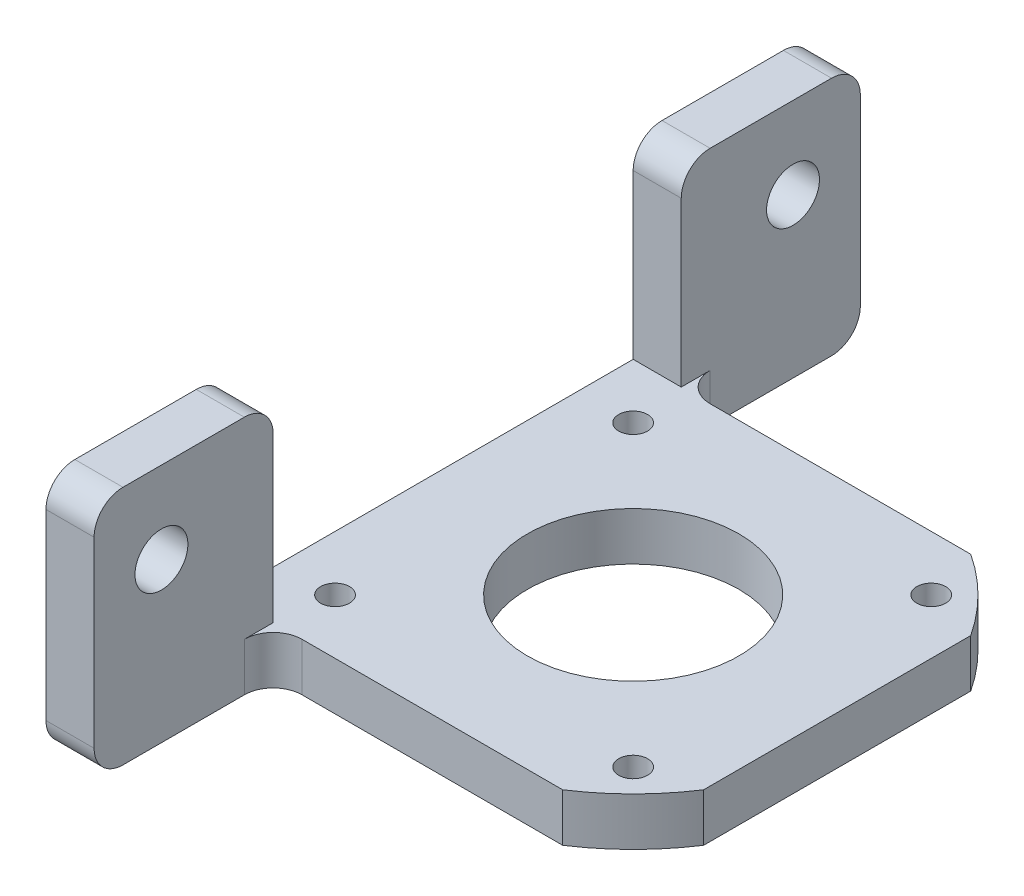
SolidWorks part; units mm, degrees
ref_plane "Front Plane" through (0, 0, 0) normal (0, 0, 1) x (1, 0, 0)
ref_plane "Top Plane" through (0, 0, 0) normal (0, 1, 0) x (1, 0, 0)
ref_plane "Right Plane" through (0, 0, 0) normal (1, 0, 0) x (0, 0, -1)
sketch "Sketch1" plane through (0, 0, 0) normal (0, 1, 0) x (1, 0, 0)
  line L0 (-13.8838, -21.209) -> (-21.209, -21.209)
  line L1 (-21.209, -21.209) -> (-21.209, -13.8838)
  line L2 (-21.209, 13.8838) -> (-21.209, 21.209)
  line L3 (-21.209, 21.209) -> (-13.8838, 21.209)
  line L5 (-21.209, -13.8838) -> (-21.209, 13.8838)
  line L6 (13.8838, 21.209) -> (-13.8838, 21.209)
  line L7 (21.209, -13.8838) -> (21.209, 13.8838)
  line L8 (13.8838, -21.209) -> (-13.8838, -21.209)
  arc A2 (21.209, 13.8838) -> (13.8838, 21.209) centre (0, 0) ccw
  arc A3 (13.8838, -21.209) -> (21.209, -13.8838) centre (0, 0) ccw
  dimension "D1" = 25.3492
  dimension "D2" = 21.209
sketch "Sketch3" plane through (0, 0, 0) normal (0, 1, 0) x (1, 0, 0)
  line L1 (21.209, -21.209) -> (-21.209, -21.209) construction
  line L2 (21.209, -21.209) -> (21.209, 21.209) construction
  line L3 (21.209, 21.209) -> (-21.209, 21.209) construction
  line L4 (-21.209, -21.209) -> (-21.209, 21.209) construction
  line L5 (21.209, -21.209) -> (-21.209, 21.209) construction
  line L6 (21.209, 21.209) -> (-21.209, -21.209) construction
  line L7 (15.494, -15.494) -> (-15.494, -15.494) construction
  line L8 (15.494, -15.494) -> (15.494, 15.494) construction
  line L9 (15.494, 15.494) -> (-15.494, 15.494) construction
  line L10 (-15.494, -15.494) -> (-15.494, 15.494) construction
  line L11 (15.494, -15.494) -> (-15.494, 15.494) construction
  line L12 (15.494, 15.494) -> (-15.494, -15.494) construction
  circle A0 centre (-15.494, 15.494) radius 1.5 construction
  circle A1 centre (15.494, 15.494) radius 1.5 construction
  circle A2 centre (-15.494, -15.494) radius 1.5 construction
  circle A3 centre (15.494, -15.494) radius 1.5 construction
  circle A4 centre (0, 0) radius 2.5 construction
  circle A5 centre (0, 0) radius 10.9982 construction
  circle A6 centre (15.494, -15.494) radius 1.5
  circle A7 centre (15.494, 15.494) radius 1.5
  circle A8 centre (-15.494, -15.494) radius 1.5
  circle A9 centre (-15.494, 15.494) radius 1.5
  circle A10 centre (0, 0) radius 10.9982
  point P0 (0, 0)
  point P6 (0, 0)
  point P18 (0, 2.5)
  point P19 (0, 21.209)
  point P20 (0, 10.9982)
  point P21 (-15.494, -16.994)
  dimension "D3" = 3
  dimension "ShaftDia" = 5
  dimension "LargeDia" = 21.9964
  dimension "Width" = 42.418
  dimension "CentertoCenter" = 30.988
extrude "Boss-Extrude1" add sketch "Sketch1" along normal blind 5 contours L6 L3 L2 L5 L1 L0 L8 A3 L7 A2
extrude "Cut-Extrude1" cut sketch "Sketch3" along normal blind 5
sketch "Sketch5" plane through (0, 0, 21.209) normal (0, 0, 1) x (1, 0, 0)
  line L0 (-21.209, 5) -> (-21.209, 0)
  line L1 (-21.209, 0) -> (-16.209, 0)
  line L2 (-16.209, 0) -> (-16.209, 5)
  line L3 (13.8838, 5) -> (-21.209, 5) construction
  line L4 (-16.209, 5) -> (-21.209, 5)
  dimension "D1" = 5
extrude "Boss-Extrude2" add sketch "Sketch5" along normal blind 18.62
ref_plane "Plane1" through (0, 0, 0) normal (0, 0, -1) x (-1, 0, 0)
sketch "Sketch6" plane through (0, 5, 0) normal (0, 1, 0) x (1, 0, 0)
  line L0 (-16.209, -21.209) -> (-21.209, -21.209)
  line L1 (-21.209, -39.829) -> (-21.209, 21.209) construction
  line L2 (-21.209, -21.209) -> (-21.209, -39.829)
  line L3 (-21.209, -39.829) -> (-16.209, -39.829)
  line L4 (-16.209, -39.829) -> (-16.209, -21.209)
extrude "Boss-Extrude3" add sketch "Sketch6" along normal blind 20
sketch "Sketch7" plane through (-16.209, 0, 0) normal (1, 0, 0) x (0, 0, -1)
  line L0 (-39.829, 0) -> (-21.209, 0) construction
  line L1 (-39.829, 0) -> (-39.829, 25) construction
  circle A0 centre (-32.829, 16.5) radius 2.75
  dimension "D3" = 5.5
  dimension "D1" = 16.5
  dimension "D2" = 7
extrude "Cut-Extrude2" cut sketch "Sketch7" against normal up to next
mirror "Mirror3" about plane through (0, 0, 0) normal (0, 0, -1) of "Boss-Extrude2", "Boss-Extrude3", "Cut-Extrude2"
fillet "Fillet1" radius 3 8 edges at (-18.709, 25, -21.209) (-18.709, 25, -39.829) (-18.709, 0, -39.829) (-18.709, 0, 39.829) (-18.709, 25, 21.209) (-18.709, 25, 39.829) (-16.209, 2.5, -21.209) (-16.209, 2.5, 21.209)
